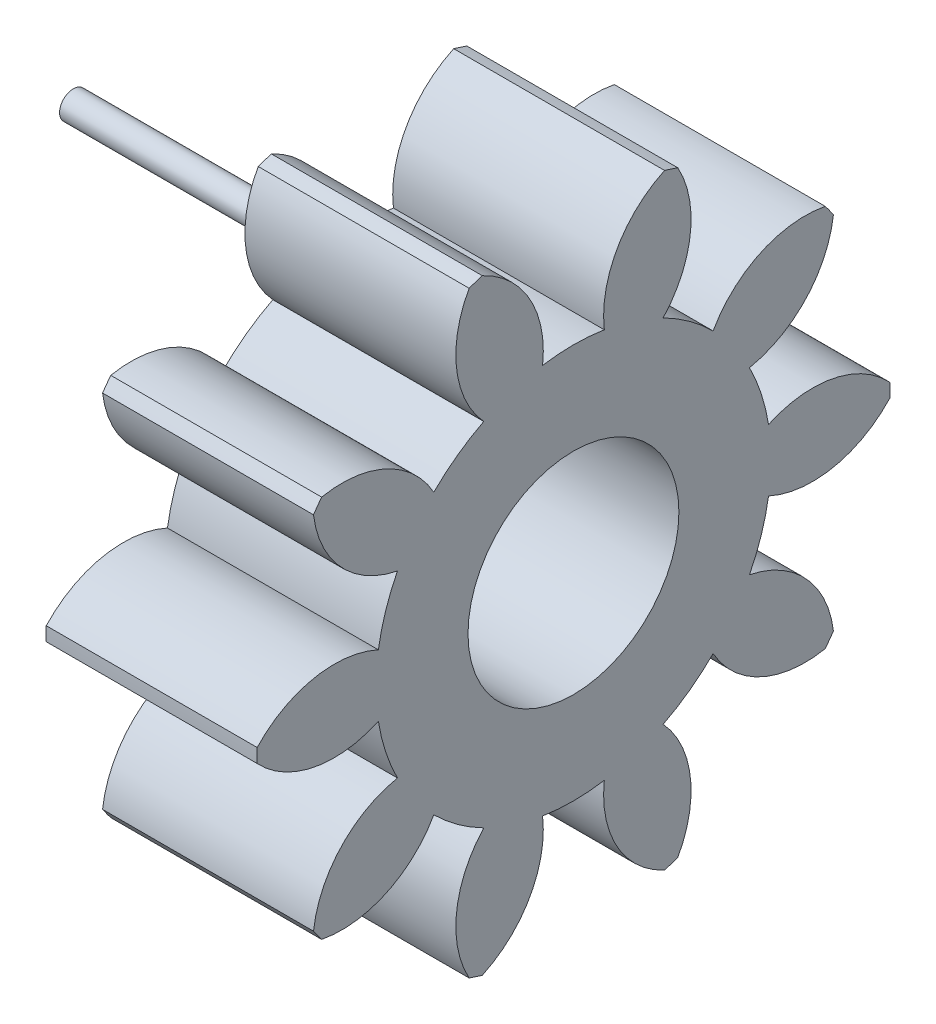
SolidWorks part; units mm, degrees
ref_plane "Plane1" through (0, 0, 0) normal (0, 0, 1) x (1, 0, 0)
ref_plane "Plane2" through (0, 0, 0) normal (0, 1, 0) x (1, 0, 0)
ref_plane "Plane3" through (0, 0, 0) normal (1, 0, 0) x (0, 0, -1)
sketch "HoldingSke" plane through (0, 0, 0) normal (0, 1, 0) x (1, 0, 0)
  line L0 (0, 0) -> (3.9392, -0.6946)
  line L1 (-15, 0) -> (100, 0) construction
  line L2 (0, 0) -> (-2.1039, 2.3779)
  line L3 (0, 0) -> (-11.863, 4.5341)
  line L4 (0, 0) -> (8.5048, 1.4996)
  line L5 (0, 0) -> (-46.8476, -17.4728)
  line L6 (0, 0) -> (-0.829, -0.5593)
  line L7 (-2.1039, 2.3779) -> (8.6586, 51.2059)
  line L8 (-76.2, 54.61) -> (-76.1, 54.61)
  line L9 (-71.009, 38.7566) -> (-53.1078, 45.2721)
  line L10 (-76.2, 71.12) -> (104.1128, 71.12)
  line L11 (0, 0) -> (-1, 0)
  line L12 (-76.2, 101.6) -> (-76.192, 101.6)
  line L13 (24.9733, 27.94) -> (52.9518, 28.4284)
  line L14 (24.9733, 27.94) -> (24.9743, 27.94)
  line L15 (24.9733, 27.94) -> (100.4006, 29.5858)
  line L16 (-63.627, -0.25) -> (-12.827, -0.25)
  circle A0 centre (0, 0) radius 0.625
  circle A1 centre (0, 0) radius 0.9365
  circle A2 centre (0, 0) radius 37.5
  circle A3 centre (0, 0) radius 0.625
  dimension "MHD" = 1.873
  dimension "Hub_dia" = 75
  dimension "Bore" = 1.25
  dimension "MBD" = 1.25
  dimension "Num_teeth" = 10
  dimension "Pitch" = 4
  dimension "Overall_len" = 50
  dimension "Show_teeth" = 10
  dimension "Thickness" = 1
  dimension "OAL" = 50.0001
  dimension "T_dim" = 0.1
  dimension "Ap" = 20
  dimension "H" = 19.05
  dimension "Pitch_radius" = 180.3128
  dimension "Width" = 1
  dimension "Backlash" = 0.008
  dimension "Addendum_fac" = 1
  dimension "Dedendum_fac" = 1.25
  dimension "Clearance_fac" = 0.25
  dimension "Dedendum_add" = 0.001
  dimension "Module" = 0.25
sketch "BasProSke" plane through (0, 0, 0) normal (0, 1, 0) x (1, 0, 0)
  line L0 (-10, 0) -> (60, 0) construction
  line L1 (0, 0) -> (0, 1.5)
  line L2 (0, 0) -> (1, 0)
  line L3 (1, 0) -> (1, 1.5)
  line L4 (1, 1.5) -> (0, 1.5)
  dimension "Thickness" = 1
  dimension "Diameter" = 3
revolve "Base-Revolve" add sketch "BasProSke" angle 360 about L0
sketch "TooCutSke" plane through (0, 0, 0) normal (1, 0, 0) x (0, 0, -1)
  line L1 (0, 0) -> (0, 107) construction
  line L2 (0, 0) -> (-0.2095, 1.2323) construction
  line L3 (0, 0) -> (-0.7644, 2.3524) construction
  line L4 (-0.2095, 1.2323) -> (-0.3822, 1.1762) construction
  arc A0 (0.1463, 0.925) -> (-0.1463, 0.925) centre (0, 0) ccw
  arc A1 (0.4686, 1.4516) -> (-0.4686, 1.4516) centre (0, 0) ccw
  circle A2 centre (0, 0) radius 1.25 construction
  circle A3 centre (0, 0) radius 1.1746 construction
  arc A4 (-0.1463, 0.925) -> (-0.4686, 1.4516) centre (-0.6429, 0.983) ccw
  arc A5 (0.4686, 1.4516) -> (0.1463, 0.925) centre (0.6429, 0.983) ccw
  dimension "Root_dia" = 1.873
  dimension "Overcut_dia" = 3.0508
  dimension "Pitch_dia" = 2.5
  dimension "Base_dia" = 2.3492
  dimension "Flank_rad" = 0.5
  dimension "Half_ang" = 18
  dimension "Half_CT" = 0.1815
extrude "ToothCut" cut sketch "TooCutSke" along normal through all
fillet "Breaks" [suppressed] radius 0.005
fillet "RootFillets" [suppressed] radius 0.0635
pattern_circular "TeethCuts" count 10 every 36 about axis through (-10, 0, 0) along (1, 0, 0) of "ToothCut", "RootFillets", "Breaks"
sketch "HubNeaOneSke" plane through (0, 0, 0) normal (-1, 0, 0) x (0, 0, 1)
  circle A0 centre (0, 0) radius 0.9365
  dimension "Diameter" = 1.873
extrude "HubNearOne" [suppressed] add sketch "HubNeaOneSke" along normal blind 49.0001
sketch "HubNeaBotSke" plane through (0, 0, 0) normal (-1, 0, 0) x (0, 0, 1)
  circle A0 centre (0, 0) radius 0.9365
  dimension "Diameter" = 1.873
extrude "HubNearBoth" [suppressed] add sketch "HubNeaBotSke" along normal blind 24.5
ref_plane "FarPln" through (1, 0, 0) normal (1, 0, 0) x (0, 0, -1)
sketch "HubFarSke" plane through (1, 0, 0) normal (1, 0, 0) x (0, 0, -1)
  circle A0 centre (0, 0) radius 0.9365
  dimension "Diameter" = 1.873
extrude "HubFar" [suppressed] add sketch "HubFarSke" along normal blind 24.5
sketch "BorSke" plane through (0, 0, 0) normal (1, 0, 0) x (0, 0, -1)
  circle A0 centre (0, 0) radius 0.5
  dimension "Diameter" = 1
extrude "Bore" cut sketch "BorSke" along normal mid plane 100.0001
sketch "KeySke" plane through (0, 0, 0) normal (1, 0, 0) x (0, 0, -1)
  line L0 (-0.05, 0) -> (-0.05, 0.725)
  line L1 (-0.05, 0.725) -> (0.05, 0.725)
  line L2 (0.05, 0.725) -> (0.05, 0)
  line L3 (0, 0) -> (0, 34) construction
  line L4 (-0.05, 0) -> (0.05, 0)
  dimension "Offset" = 0.725
extrude "Keyway" [suppressed] cut sketch "KeySke" along normal mid plane 100.0001
pattern_circular "Keyway2" [suppressed] count 2 every 90 about axis through (-10, 0, 0) along (1, 0, 0)
sketch "草圖1" plane through (1, 0, 0) normal (1, 0, 0) x (0, 0, -1)
  circle A0 centre (-0.3714, 1.1083) radius 0.065
  dimension "D1" = 0.13
extrude "填料-伸長2" add sketch "草圖1" against normal blind 2 contours A0
equation "' \"Module@HoldingSke\" = 6.35"
equation "' \"Num_teeth@HoldingSke\" = 12"
equation "' \"Ap@HoldingSke\" =  20"
equation "' \"Ap@HoldingSke\" = 20"
equation "' \"Width@HoldingSke\" = 0.5 * 25.4"
equation "' \"Hub_dia@HoldingSke\"= 1 * 25.4"
equation "' \"Hub_dia@HoldingSke\" = 1 * 25.4"
equation "' \"Overall_len@HoldingSke\" = 1.0 * 25.4"
equation "' \"Bore@HoldingSke\" = 0.75 * 25.4"
equation "' \"T_dim@HoldingSke\" = 0.1 * 25.4"
equation "' \"Width@KeySke\" = 0.25 * 25.4"
equation "' \"Show_teeth@HoldingSke\" = 13"
equation "' \"Backlash@HoldingSke\" = 0.009 * 25.4"
equation "' \"Addendum_fac@HoldingSke\" = 1.0"
equation "' \"Dedendum_fac@HoldingSke\" = 1.25"
equation "' \"Dedendum_add@HoldingSke\" = 0.00005 * 25.4"
equation "' \"Clearance_fac@HoldingSke\" = 0.25"
equation "\"Pitch@HoldingSke\" = 1 / \"Module@HoldingSke\""
equation "\"Overcut_dia@TooCutSke\" = (\"Num_teeth@HoldingSke\" + 2 * \"Addendum_fac@HoldingSke\") / \"Pitch@HoldingSke\" + 0.002 * 25.4"
equation "\"Pitch_dia@TooCutSke\" = \"Num_teeth@HoldingSke\" / \"Pitch@HoldingSke\""
equation "\"Base_dia@TooCutSke\" = \"Num_teeth@HoldingSke\" / \"Pitch@HoldingSke\" * cos((\"Ap@HoldingSke\"  * 3.14159265 / 180))"
equation "\"Root_dia@TooCutSke\" = (\"Num_teeth@HoldingSke\" + 2) / \"Pitch@HoldingSke\" - 2 * (\"Addendum_fac@HoldingSke\" + \"Dedendum_fac@HoldingSke\") / \"Pitch@HoldingSke\" - \"Dedendum_add@HoldingSke\" * 2"
equation "\"Half_ang@TooCutSke\" = 180 / \"Num_teeth@HoldingSke\""
equation "\"Half_CT@TooCutSke\" = \"Num_teeth@HoldingSke\" / \"Pitch@HoldingSke\" * sin((3.14159265 / 2 / \"Num_teeth@HoldingSke\")) / 2 - 7 * \"Backlash@HoldingSke\" / 4"
equation "\"Flank_rad@TooCutSke\" = \"Num_teeth@HoldingSke\" / \"Pitch@HoldingSke\" / 5"
equation "\"Radius@RootFillets\" = \"Clearance_fac@HoldingSke\" / \"Pitch@HoldingSke\" + \"Dedendum_add@HoldingSke\""
equation "\"Break_rad@Breaks\" = 0.02 / \"Pitch@HoldingSke\""
equation "\"Thickness@HoldingSke\" = \"Width@HoldingSke\""
equation "\"OAL@HoldingSke\" = \"Thickness@HoldingSke\""
equation "\"MHD@HoldingSke\" = (\"Num_teeth@HoldingSke\" + 2) / \"Pitch@HoldingSke\" - 2 * (\"Addendum_fac@HoldingSke\" + \"Dedendum_fac@HoldingSke\")  / \"Pitch@HoldingSke\" - \"Dedendum_add@HoldingSke\" * 2"
equation "\"MBD@HoldingSke\" = (\"Num_teeth@HoldingSke\" + 2) / \"Pitch@HoldingSke\" - 2 * (\"Addendum_fac@HoldingSke\" + \"Dedendum_fac@HoldingSke\")  / \"Pitch@HoldingSke\" - \"Dedendum_add@HoldingSke\" * 2 - 0.002 * 25.4"
equation "\"MHD@HoldingSke\" = ((sgn( \"MHD@HoldingSke\" - \"Hub_dia@HoldingSke\" )-1)*( \"MHD@HoldingSke\" - \"Hub_dia@HoldingSke\" ))/-2+ \"Hub_dia@HoldingSke\""
equation "\"MBD@HoldingSke\" = ((sgn( \"MBD@HoldingSke\" - \"Bore@HoldingSke\" )-1)*( \"MBD@HoldingSke\" - \"Bore@HoldingSke\" ))/-2+ \"Bore@HoldingSke\""
equation "\"OAL@HoldingSke\" = ((sgn( \"OAL@HoldingSke\" - \"Overall_len@HoldingSke\" )+1)*( \"OAL@HoldingSke\" - \"Overall_len@HoldingSke\" ))/2 + \"Overall_len@HoldingSke\" + 0.000002 * 25.4"
equation "\"Num_teeth@TeethCuts\" = int( \"Show_teeth@HoldingSke\" ) + 1"
equation "\"Num_teeth@TeethCuts\" = ((sgn( \"Num_teeth@TeethCuts\" - \"Num_teeth@HoldingSke\" )-1)*( \"Num_teeth@TeethCuts\" - \"Num_teeth@HoldingSke\" ))/-2+ \"Num_teeth@HoldingSke\""
equation "\"Num_teeth@TeethCuts\" = ((sgn( \"Num_teeth@TeethCuts\" - 2.0)+1)*( \"Num_teeth@TeethCuts\" - 2.0))/2 +2.0"
equation "\"Angle@TeethCuts\" = 360.0 / \"Num_teeth@HoldingSke\""
equation "\"Diameter@BasProSke\" = (\"Num_teeth@HoldingSke\" + 2 * \"Addendum_fac@HoldingSke\") / \"Pitch@HoldingSke\""
equation "\"Thickness@BasProSke\"  = \"Thickness@HoldingSke\""
equation "' \"Fillet_rad@BasProSke\" =  \"Thickness@HoldingSke\" * 0.05"
equation "' \"Fillet_rad@BasProSke\" = \"Thickness@HoldingSke\" * 0.05"
equation "\"MHD@HoldingSke\" = ((sgn( \"MHD@HoldingSke\" - \"Root_dia@TooCutSke\" )-1)*( \"MHD@HoldingSke\" - \"Root_dia@TooCutSke\" ))/-2+ \"Root_dia@TooCutSke\""
equation "\"Diameter@HubNeaOneSke\" = \"MHD@HoldingSke\""
equation "\"Length@HubNearOne\" = \"OAL@HoldingSke\" - \"Thickness@BasProSke\""
equation "\"Diameter@HubNeaBotSke\" = \"MHD@HoldingSke\""
equation "\"Length@HubNearBoth\" = ( \"OAL@HoldingSke\" - \"Thickness@BasProSke\" ) / 2.0"
equation "\"Thickness@FarPln\" = \"Thickness@BasProSke\""
equation "\"Diameter@HubFarSke\" = \"MHD@HoldingSke\""
equation "\"Length@HubFar\" = ( \"OAL@HoldingSke\" - \"Thickness@BasProSke\" ) / 2.0"
equation "\"D1@Bore\" = \"OAL@HoldingSke\" * 2.0"
equation "\"D1@Keyway\" = \"OAL@HoldingSke\" * 2.0"
equation "\"Offset@KeySke\" = \"T_dim@HoldingSke\" + \"MBD@HoldingSke\" / 2.0"
